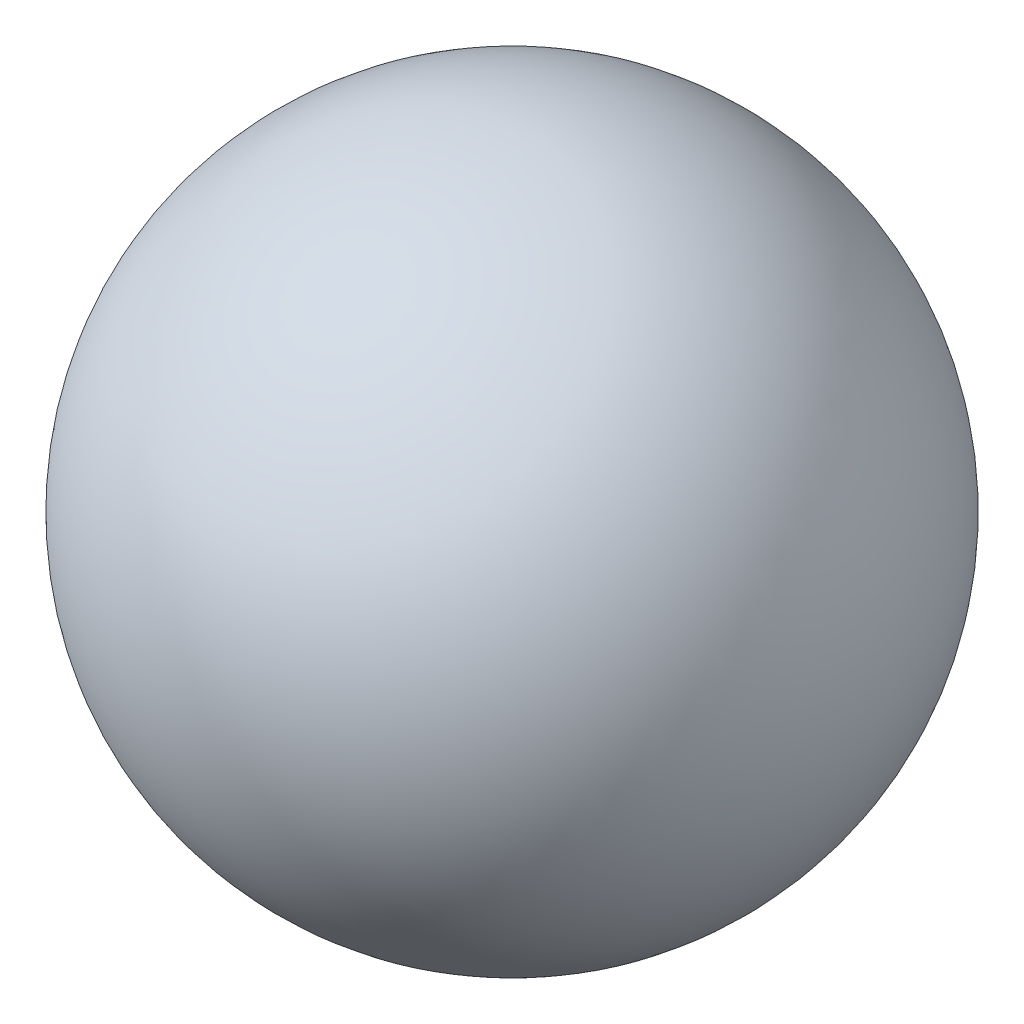
SolidWorks part; units mm, degrees
ref_plane "Front Plane" through (0, 0, 0) normal (0, 0, 1) x (1, 0, 0)
ref_plane "Top Plane" through (0, 0, 0) normal (0, 1, 0) x (1, 0, 0)
ref_plane "Right Plane" through (0, 0, 0) normal (1, 0, 0) x (0, 0, -1)
sketch "Sketch1" plane through (0, 0, 0) normal (0, 0, 1) x (1, 0, 0)
  line L0 (0, 6.35) -> (0, -6.35)
  arc A0 (0, -6.35) -> (0, 6.35) centre (0, 0) ccw
  dimension "D1" = 12.7
revolve "Revolve1" add sketch "Sketch1" angle 360 about L0
